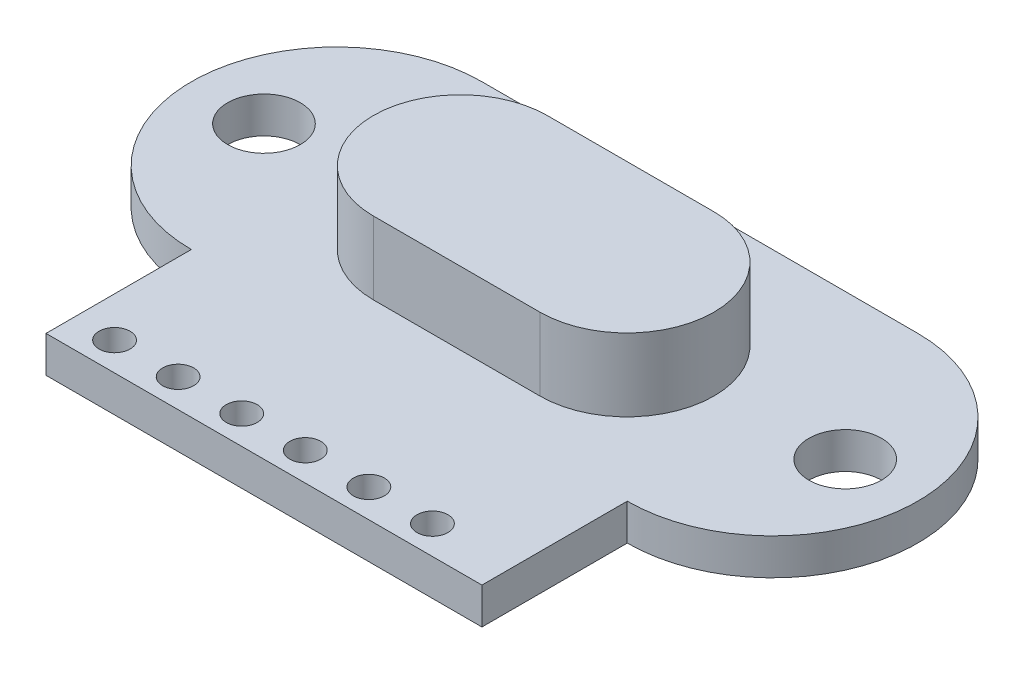
SolidWorks part; units mm, degrees
ref_plane "Front Plane" through (0, 0, 0) normal (0, 0, 1) x (1, 0, 0)
ref_plane "Top Plane" through (0, 0, 0) normal (0, 1, 0) x (1, 0, 0)
ref_plane "Right Plane" through (0, 0, 0) normal (1, 0, 0) x (0, 0, -1)
sketch "Sketch1" plane through (0, 0, 0) normal (0, 1, 0) x (1, 0, 0)
  line L0 (-6, 8) -> (6, 8) construction
  line L1 (-6, 12) -> (6, 12)
  line L2 (-6, 4) -> (6, 4)
  line L3 (0, 8) -> (0, 0) construction
  arc A0 (-6, 12) -> (-6, 4) centre (-6, 8) ccw
  arc A1 (6, 4) -> (6, 12) centre (6, 8) ccw
  point P2 (0, 8)
  dimension "D2" = 20
  dimension "D1" = 12
  dimension "D3" = 8
extrude "Boss-Extrude1" add sketch "Sketch1" along normal blind 1
sketch "Sketch2" plane through (0, 0, 0) normal (0, -1, 0) x (1, 0, 0)
  line L1 (-6, -4) -> (6, -4)
  line L2 (-6, -4) -> (-6, 0)
  line L3 (-6, 0) -> (6, 0)
  line L4 (6, -4) -> (6, 0)
extrude "Boss-Extrude2" add sketch "Sketch2" against normal blind 1
sketch "Sketch3" plane through (0, 1, 0) normal (0, 1, 0) x (1, 0, 0)
  line L0 (-8, 8) -> (8, 8) construction
  line L1 (0, 4) -> (0, 8) construction
  circle A0 centre (8, 8) radius 1
  circle A1 centre (-8, 8) radius 1
  circle A2 centre (-4.8957, 0.7833) radius 0.4268
  circle A8 centre (-3.1457, 0.7833) radius 0.4268
  circle A9 centre (-1.3957, 0.7833) radius 0.4268
  circle A10 centre (0.3543, 0.7833) radius 0.4268
  circle A11 centre (2.1043, 0.7833) radius 0.4268
  circle A12 centre (3.8543, 0.7833) radius 0.4268
  point P11 (0, 0)
  dimension "D1" = 2
  dimension "D4" = 6
  dimension "D2" = 4
  dimension "D3" = 16
extrude "Cut-Extrude1" cut sketch "Sketch3" against normal through all
sketch "Sketch4" plane through (0, 1, 0) normal (0, 1, 0) x (1, 0, 0)
  line L0 (-2.294, 7.6988) -> (2.294, 7.6988) construction
  line L1 (-2.294, 10.0931) -> (2.294, 10.0931)
  line L2 (-2.294, 5.3044) -> (2.294, 5.3044)
  line L3 (0, 7.6988) -> (0, 0) construction
  arc A0 (-2.294, 10.0931) -> (-2.294, 5.3044) centre (-2.294, 7.6988) ccw
  arc A1 (2.294, 5.3044) -> (2.294, 10.0931) centre (2.294, 7.6988) ccw
  point P2 (0, 7.6988)
extrude "Boss-Extrude3" add sketch "Sketch4" along normal blind 2
sketch "Sketch5" plane through (0, 0, 0) normal (0, -1, 0) x (1, 0, 0)
  line L1 (-4.4007, -4.2879) -> (4.1466, -4.2879)
  line L2 (-4.4007, -4.2879) -> (-4.4007, -9.6116)
  line L3 (-4.4007, -9.6116) -> (4.1466, -9.6116)
  line L4 (4.1466, -4.2879) -> (4.1466, -9.6116)
extrude "Boss-Extrude4" add sketch "Sketch5" along normal blind 1
